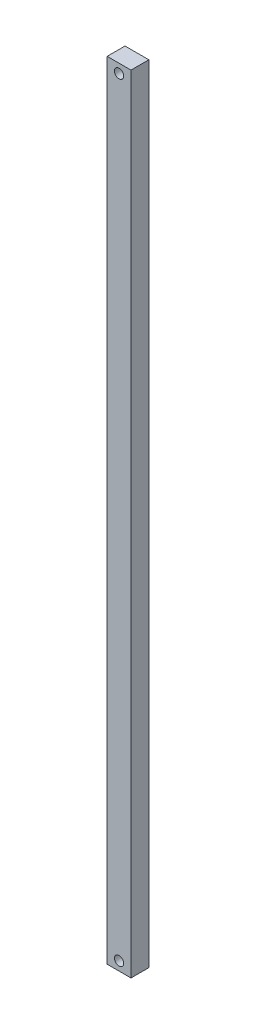
SolidWorks part; units mm, degrees
ref_plane "Front Plane" through (0, 0, 0) normal (0, 0, 1) x (1, 0, 0)
ref_plane "Top Plane" through (0, 0, 0) normal (0, 1, 0) x (1, 0, 0)
ref_plane "Right Plane" through (0, 0, 0) normal (1, 0, 0) x (0, 0, -1)
sketch "Sketch1" plane through (0, 0, 0) normal (0, 1, 0) x (1, 0, 0)
  line L1 (-6.7189, 7.5298) -> (5.9811, 7.5298)
  line L2 (-6.7189, 7.5298) -> (-6.7189, -1.9952)
  line L3 (-6.7189, -1.9952) -> (5.9811, -1.9952)
  line L4 (5.9811, 7.5298) -> (5.9811, -1.9952)
  dimension "D1" = 12.7
  dimension "D2" = 9.525
extrude "Boss-Extrude1" add sketch "Sketch1" along normal blind 419.1
hole_wizard "CBORE for #8 Socket Head Cap Screw1" positions "Sketch3" profile "Sketch2" counterbore size "#8" standard "ANSI Inch" end condition through all
sketch "Sketch3" plane through (0, 0, -7.5298) normal (0, 0, -1) x (-1, 0, 0)
  line L0 (6.7189, 419.1) -> (6.7189, 0) construction
  line L1 (-5.9811, 419.1) -> (6.7189, 419.1) construction
  line L2 (-5.9811, 0) -> (6.7189, 0) construction
  point P0 (0.3689, 414.3375)
  point P2 (0.3689, 4.7625)
  dimension "D1" = 6.35
  dimension "D2" = 4.7625
  dimension "D3" = 6.35
  dimension "D4" = 4.7625
sketch "Sketch2" plane through (-0.3689, 414.3375, -7.5298) normal (1, 0, 0) x (0, 1, 0)
  line L0 (0, 0) -> (0, 9.525)
  line L1 (0, 9.525) -> (2.4574, 9.525)
  line L3 (2.4574, 9.525) -> (2.4575, 4.1656)
  line L4 (2.4575, 4.1656) -> (3.9687, 4.1656)
  line L5 (3.9687, 4.1656) -> (3.9687, 0)
  line L7 (3.9687, 0) -> (0, 0)
  line L11 (0, -6.35) -> (0, 107.95) construction
  dimension "Thru Hole Dia." = 4.9149
  dimension "Thru Hole Depth" = 9.525
  dimension "C'Bore Dia." = 7.9375
  dimension "C'Bore Depth" = 4.1656
